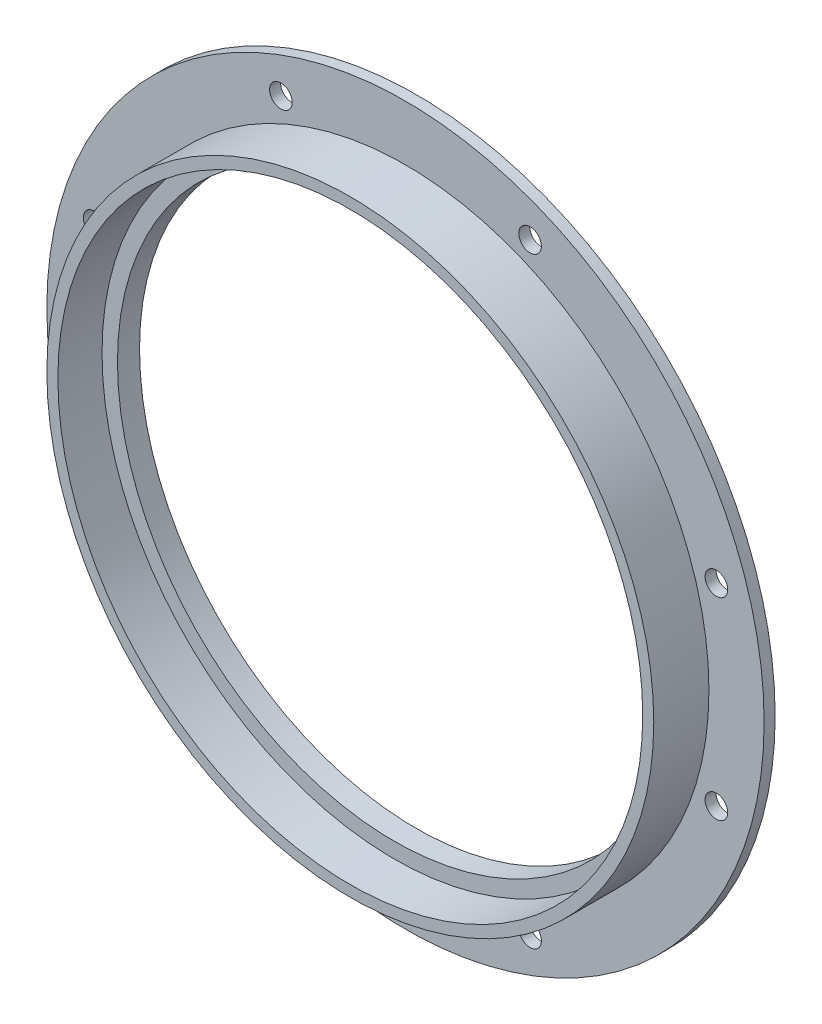
SolidWorks part; units mm, degrees
material "1060 合金"
ref_plane "前视基准面" through (0, 0, 0) normal (0, 0, 1) x (1, 0, 0)
ref_plane "上视基准面" through (0, 0, 0) normal (0, 1, 0) x (1, 0, 0)
ref_plane "右视基准面" through (0, 0, 0) normal (1, 0, 0) x (0, 0, -1)
other "Configuration Table"
sketch "草图1" plane through (0, 0, 0) normal (0, 0, 1) x (1, 0, 0)
  line L0 (0, 65) -> (0, 59) construction
  circle A0 centre (0, 0) radius 50.2
  circle A1 centre (0, 0) radius 59 construction
  circle A2 centre (0, 0) radius 53 construction
  circle A3 centre (0, 59) radius 0.5
  circle A4 centre (29.5, 51.0955) radius 0.5
  circle A5 centre (51.0955, 29.5) radius 0.5
  circle A6 centre (59, 0) radius 0.5
  circle A7 centre (51.0955, -29.5) radius 0.5
  circle A8 centre (29.5, -51.0955) radius 0.5
  circle A9 centre (0, -59) radius 0.5
  circle A10 centre (-29.5, -51.0955) radius 0.5
  circle A11 centre (0, 0) radius 45 construction
  circle A12 centre (0, 0) radius 65
  circle A13 centre (-51.0955, -29.5) radius 0.5
  circle A14 centre (-59, 0) radius 0.5
  circle A15 centre (-51.0955, 29.5) radius 0.5
  circle A16 centre (-29.5, 51.0955) radius 0.5
  point P24 (0, 0)
  dimension "D1" = 1
  dimension "D3" = 2.8
  dimension "D4" = 106
  dimension "D5" = 90
  dimension "D6" = 130
  dimension "D7" = 6
  dimension "D2" = 12
extrude "凸台-拉伸1" add sketch "草图1" along normal blind 10
sketch "草图2" plane through (0, 0, 0) normal (0, 0, -1) x (-1, 0, 0)
  circle A0 centre (0, 0) radius 53
  dimension "D1" = 106
extrude "切除-拉伸1" cut sketch "草图2" against normal offset from surface (8 mm away) 2 up to face at (-50.5955, 29.5, 10)
sketch "草图9" plane through (0, 0, 10) normal (0, 0, 1) x (1, 0, 0)
  circle A0 centre (0, 0) radius 55
  circle A1 centre (0, 0) radius 65 construction
  circle A2 centre (0, 0) radius 65
  dimension "D1" = 110
extrude "切除-拉伸2" cut sketch "草图9" against normal blind 8
sketch "草图11" plane through (0, 0, 2) normal (0, 0, 1) x (1, 0, 0)
  circle A0 centre (0, 0) radius 55
  circle A1 centre (0, 0) radius 55 construction
  circle A2 centre (0, 0) radius 65 construction
  circle A3 centre (0, 0) radius 65
extrude "切除-拉伸4" cut sketch "草图11" against normal mid plane 30
sketch "草图12" plane through (0, 0, 8) normal (0, 0, -1) x (-1, 0, 0)
  circle A1 centre (0, 0) radius 53
  circle A2 centre (0, 0) radius 53
  dimension "D1" = 0
extrude "切除-拉伸6" cut sketch "草图12" against normal mid plane 30
sketch "草图13" plane through (0, 0, 0) normal (0, 0, -1) x (-1, 0, 0)
  circle A0 centre (0, 0) radius 50.2
  circle A1 centre (0, 0) radius 53 construction
  circle A2 centre (0, 0) radius 55 construction
  circle A3 centre (0, 0) radius 55
  dimension "D1" = 2.8
extrude "凸台-拉伸2" add sketch "草图13" along normal mid plane 4
sketch "草图14" plane through (0, 0, -2) normal (0, 0, -1) x (-1, 0, 0)
  line L0 (0, 59) -> (0, 0) construction
  line L1 (0, 0) -> (22.5783, 54.5089) construction
  line L3 (-56.3449, -17.5) -> (56.3449, -17.5) construction
  line L4 (-56.3449, -17.5) -> (-56.3449, 17.5) construction
  line L5 (-56.3449, 17.5) -> (56.3449, 17.5) construction
  line L6 (56.3449, -17.5) -> (56.3449, 17.5) construction
  line L7 (-56.3449, -17.5) -> (56.3449, 17.5) construction
  line L8 (-56.3449, 17.5) -> (56.3449, -17.5) construction
  circle A0 centre (0, 0) radius 59 construction
  circle A1 centre (0, 0) radius 65
  circle A2 centre (22.5783, 54.5089) radius 2.05
  circle A5 centre (22.5783, -54.5089) radius 2.05
  circle A6 centre (-22.5783, -54.5089) radius 2.05
  circle A9 centre (-22.5783, 54.5089) radius 2.05
  circle A14 centre (0, 0) radius 50.2 construction
  circle A15 centre (0, 0) radius 50.2
  circle A16 centre (-54.5089, 22.5783) radius 2.05 [skipped]
  circle A17 centre (-54.5089, -22.5783) radius 2.05 [skipped]
  circle A18 centre (54.5089, 22.5783) radius 2.05 [skipped]
  circle A19 centre (54.5089, -22.5783) radius 2.05 [skipped]
  circle A20 centre (-56.3449, 17.5) radius 2.05
  circle A21 centre (-56.3449, -17.5) radius 2.05
  circle A22 centre (56.3449, 17.5) radius 2.05
  circle A23 centre (56.3449, -17.5) radius 2.05
  point P23 (0, 0)
  dimension "D1" = 118
  dimension "D2" = 130
  dimension "D3" = 8
  dimension "D4" = 4.1
  dimension "D6" = 35
  dimension "D5" = 22.5
extrude "凸台-拉伸3" add sketch "草图14" against normal blind 2
